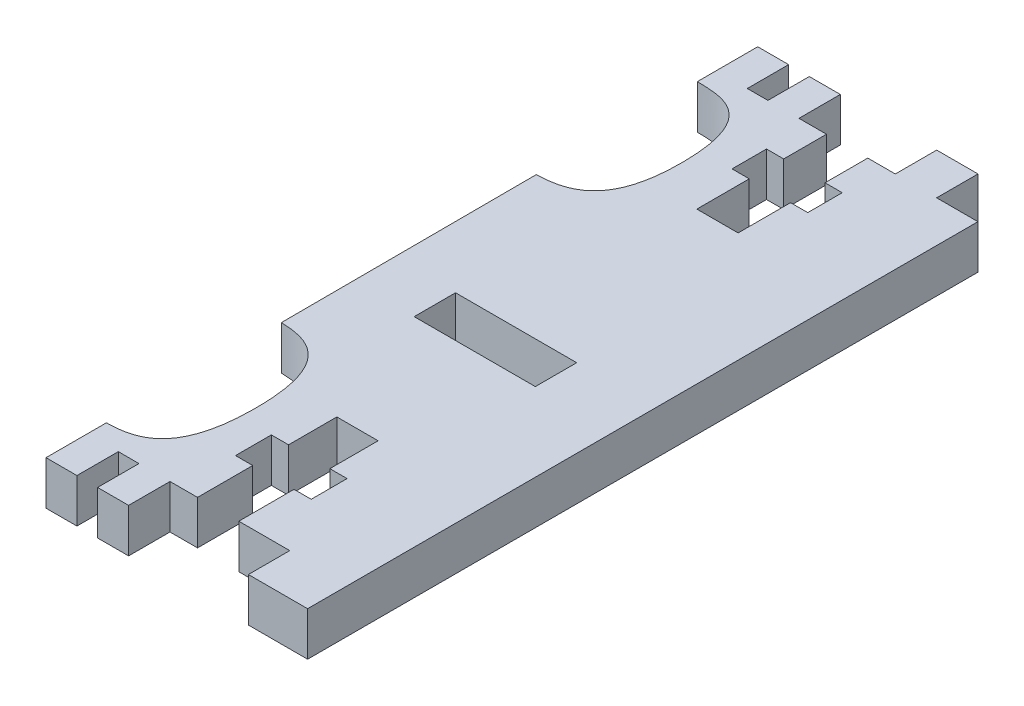
SolidWorks part; units mm, degrees
material "Acrylic (Medium-high impact)"
ref_plane "Front Plane" through (0, 0, 0) normal (0, 0, 1) x (1, 0, 0)
ref_plane "Top Plane" through (0, 0, 0) normal (0, 1, 0) x (1, 0, 0)
ref_plane "Right Plane" through (0, 0, 0) normal (1, 0, 0) x (0, 0, -1)
sketch "Sketch1" plane through (0, 0, 0) normal (0, 1, 0) x (1, 0, 0)
  line L0 (-9.4831, -21.4709) -> (-9.4831, -25.851)
  line L1 (-9.4831, 21.3709) -> (-9.4831, 25.751)
  line L2 (-9.4831, 25.751) -> (-7.2402, 25.751)
  line L3 (6.4884, 25.751) -> (6.4884, 22.7509)
  line L4 (6.4884, 22.7509) -> (9.4831, 22.7509)
  line L5 (9.4831, 22.7509) -> (9.4831, -25.851)
  line L6 (-9.4831, -25.851) -> (-7.2402, -25.851)
  line L7 (-4.9911, -0.65) -> (-4.9911, -3.6501)
  line L8 (-4.9911, -3.6501) -> (3.7933, -3.6501)
  line L9 (3.7933, -3.6501) -> (3.7933, -0.65)
  line L10 (3.7933, -0.65) -> (-4.9911, -0.65)
  line L11 (-3.4938, -25.851) -> (-3.4938, -22.8508)
  line L12 (-3.4938, -22.8508) -> (-1.4973, -22.8508)
  line L13 (-1.4973, -22.8508) -> (-1.4973, -18.8507)
  line L14 (-1.4973, -18.8507) -> (-2.745, -18.8507)
  line L15 (-2.745, -18.8507) -> (-2.745, -18.7507)
  line L16 (-2.745, -18.7507) -> (-2.745, -16.2506)
  line L17 (-2.745, -16.2506) -> (-1.4973, -16.2506)
  line L18 (-1.4973, -16.2506) -> (-1.4973, -12.7504)
  line L19 (-1.4973, -12.7504) -> (1.4972, -12.7504)
  line L20 (1.4972, -12.7504) -> (1.4972, -16.2506)
  line L21 (1.4972, -16.2506) -> (2.745, -16.2506)
  line L22 (2.745, -16.2506) -> (2.745, -18.7507)
  line L23 (2.745, -18.7507) -> (2.745, -18.8507)
  line L24 (2.745, -18.8507) -> (1.4972, -18.8507)
  line L25 (1.4972, -18.8507) -> (1.4972, -22.8508)
  line L26 (1.4972, -22.8508) -> (5.1908, -22.8508)
  line L27 (5.1908, -22.8508) -> (5.1908, -25.851)
  line L28 (3.4937, 25.751) -> (3.4937, 22.7509)
  line L29 (3.4937, 22.7509) -> (1.4972, 22.7509)
  line L30 (1.4972, 22.7509) -> (1.4972, 19.6507)
  line L31 (1.4972, 19.6507) -> (2.7451, 19.6507)
  line L32 (2.7451, 19.6507) -> (2.7451, 17.1507)
  line L33 (2.7451, 17.1507) -> (1.4972, 17.1507)
  line L34 (1.4972, 17.1507) -> (1.4972, 13.3504)
  line L35 (1.4972, 13.3504) -> (-1.4973, 13.3504)
  line L36 (-1.4973, 13.3504) -> (-1.4973, 17.1507)
  line L37 (-1.4973, 17.1507) -> (-2.745, 17.1507)
  line L38 (-2.745, 17.1507) -> (-2.745, 19.6507)
  line L39 (-2.745, 19.6507) -> (-1.4973, 19.6507) construction
  line L40 (-1.4973, 19.6507) -> (-1.4973, 22.7509)
  line L41 (-1.4973, 22.7509) -> (-3.4938, 22.7509)
  line L42 (-3.4938, 22.7509) -> (-3.4938, 25.751)
  line L43 (-7.2402, 25.751) -> (-7.3857, 25.8302)
  line L44 (-5.7428, 25.751) -> (-5.7428, 22.7509)
  line L45 (-5.7428, 22.7509) -> (-7.2402, 22.7509)
  line L46 (-7.2402, 22.7509) -> (-7.2402, 25.751)
  line L47 (-7.2402, -22.8508) -> (-5.7428, -22.8508)
  line L48 (-5.7428, -22.8508) -> (-5.7428, -25.851)
  line L49 (-5.7428, -25.851) -> (-3.4938, -25.851)
  line L50 (-7.2402, -25.851) -> (-7.2402, -22.8508)
  line L51 (-5.7428, 25.751) -> (-3.4938, 25.751)
  line L52 (-3.4938, 25.751) -> (-3.5802, 25.8302)
  line L53 (3.4937, 25.751) -> (6.4884, 25.751)
  line L54 (-9.4831, 9.693) -> (-9.4312, -8.8341)
  line L55 (5.1908, -25.851) -> (9.4831, -25.851)
  spline S1 degree 3 poles (-9.4312, -8.8341) (-7.1882, -8.8985) (-4.9654, -9.6433) (-4.9951, -15.2629) knots 1 1 1 1 2 2 2 2
  spline S2 degree 3 poles (-4.9951, -15.2629) (-5.0248, -20.8823) (-7.4265, -21.4438) (-9.4831, -21.4709) knots 2 2 2 2 3 3 3 3
  spline S4 degree 3 poles (-9.4831, 9.693) (-7.2402, 9.7574) (-4.8898, 10.4982) (-4.9525, 15.8863) knots 5 5 5 5 6 6 6 6
  spline S5 degree 3 poles (-4.9525, 15.8863) (-5.0152, 21.2742) (-7.4265, 21.3438) (-9.4831, 21.3709) knots 6 6 6 6 7 7 7 7
extrude "Boss-Extrude1" add sketch "Sketch1" along normal blind 3.175 contours S5 S4 L54 S1 S2 L0 L6 L50 L47 L48 L49 L11 L12 L13 L14 L15 L16 L17 L18 L19 L20 L21 L22 L23 L24 L25 L26 L27 L55 L5 L4 L3 L53 L28 L29 L30 L31 L32 L33 L34 L35 L36 L37 L38 L39 L40 L41 L42 L51 L44 L45
